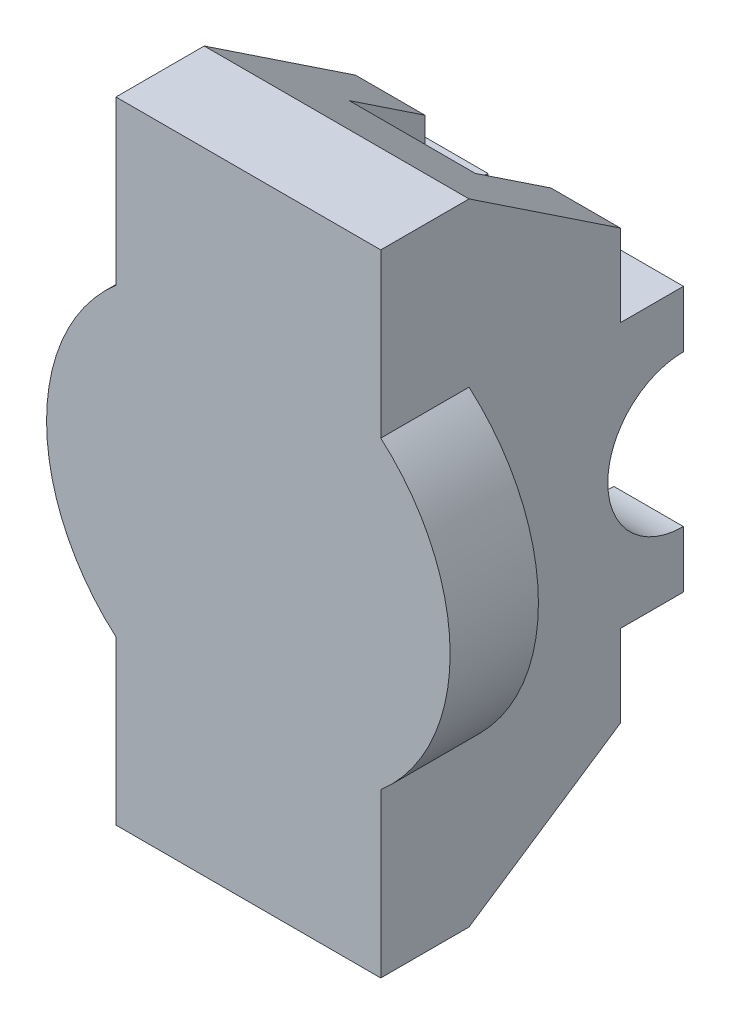
SolidWorks part; units mm, degrees
ref_plane "Front Plane" through (0, 0, 0) normal (0, 0, 1) x (1, 0, 0)
ref_plane "Top Plane" through (0, 0, 0) normal (0, 1, 0) x (1, 0, 0)
ref_plane "Right Plane" through (0, 0, 0) normal (1, 0, 0) x (0, 0, -1)
sketch "Sketch1" plane through (0, 0, 0) normal (0, 0, 1) x (1, 0, 0)
  line L1 (-21, -50) -> (21, -50)
  line L2 (-21, -50) -> (-21, 50)
  line L3 (-21, 50) -> (21, 50)
  line L4 (21, -50) -> (21, 50)
  line L5 (-21, -50) -> (21, 50) construction
  line L6 (-21, 50) -> (21, -50) construction
  point P0 (0, 0)
  point P6 (0, 0)
  dimension "D1" = 42
  dimension "D2" = 100
extrude "Boss-Extrude2" add sketch "Sketch1" along normal blind 14
sketch "Sketch3" plane through (0, 0, 14) normal (0, 0, 1) x (1, 0, 0)
  line L0 (-21, 41.5) -> (-21, 24.1454) construction
  line L1 (-21, 50) -> (-21, -50) construction
  line L2 (21, 33.7758) -> (21, 24.1454) construction
  line L3 (21, -50) -> (21, 50) construction
  line L4 (-21, -24.1454) -> (-21, -42.764) construction
  line L5 (21, -24.1454) -> (21, -42.764) construction
  line L6 (-21, 24.1454) -> (-21, -24.1454)
  line L7 (21, 24.1454) -> (21, -24.1454)
  arc A0 (-21, 24.1454) -> (-21, -24.1454) centre (0, 0) ccw
  arc A1 (21, -24.1454) -> (21, 24.1454) centre (0, 0) ccw
extrude "Boss-Extrude3" add sketch "Sketch3" against normal blind 14
sketch "Sketch4" plane through (21, 0, 0) normal (1, 0, 0) x (0, 0, -1)
  line L0 (-14, 0) -> (34, 0) construction
  line L1 (-14, 24.1454) -> (-14, -24.1454) construction
  line L2 (34, 12) -> (34, 21)
  line L3 (34, -12) -> (34, -21)
  line L4 (34, 21) -> (24, 21)
  line L5 (34, -21) -> (24, -21)
  line L6 (24, 21) -> (24, 34)
  line L7 (24, -21) -> (24, -34)
  line L8 (24, 34) -> (0, 50)
  line L9 (0, 50) -> (0, -50)
  line L10 (0, -50) -> (24, -34)
  arc A0 (34, 12) -> (34, -12) centre (34, 0) ccw
  dimension "D2" = 9
  dimension "D1" = 9
  dimension "D3" = 10
  dimension "D4" = 10
  dimension "D5" = 13
  dimension "D6" = 13
extrude "Boss-Extrude4" add sketch "Sketch4" against normal blind 11
mirror "Mirror1" about plane through (0, 0, 0) normal (1, 0, 0) of "Boss-Extrude4"
sketch "Sketch11" plane through (0, 50, 0) normal (0, 1, 0) x (1, 0, 0)
  line L0 (-10, 0) -> (-10, 12)
  line L1 (-10, 24) -> (-10, 0) construction
  line L2 (-10, 12) -> (10, 12)
  line L3 (10, 24) -> (10, 0) construction
  line L4 (10, 12) -> (10, 0)
  line L5 (10, 0) -> (-10, 0)
extrude "Boss-Extrude5" add sketch "Sketch11" against normal through all
sketch "Sketch12" plane through (10, 0, 0) normal (1, 0, 0) x (0, 0, -1)
  line L0 (0, 50) -> (12, 42)
  line L1 (12, 42) -> (12, 50)
  line L2 (12, 50) -> (0, 50)
extrude "Cut-Extrude1" cut sketch "Sketch12" against normal through all
mirror "Mirror2" about plane through (0, 0, 0) normal (0, 1, 0) of "Cut-Extrude1"
